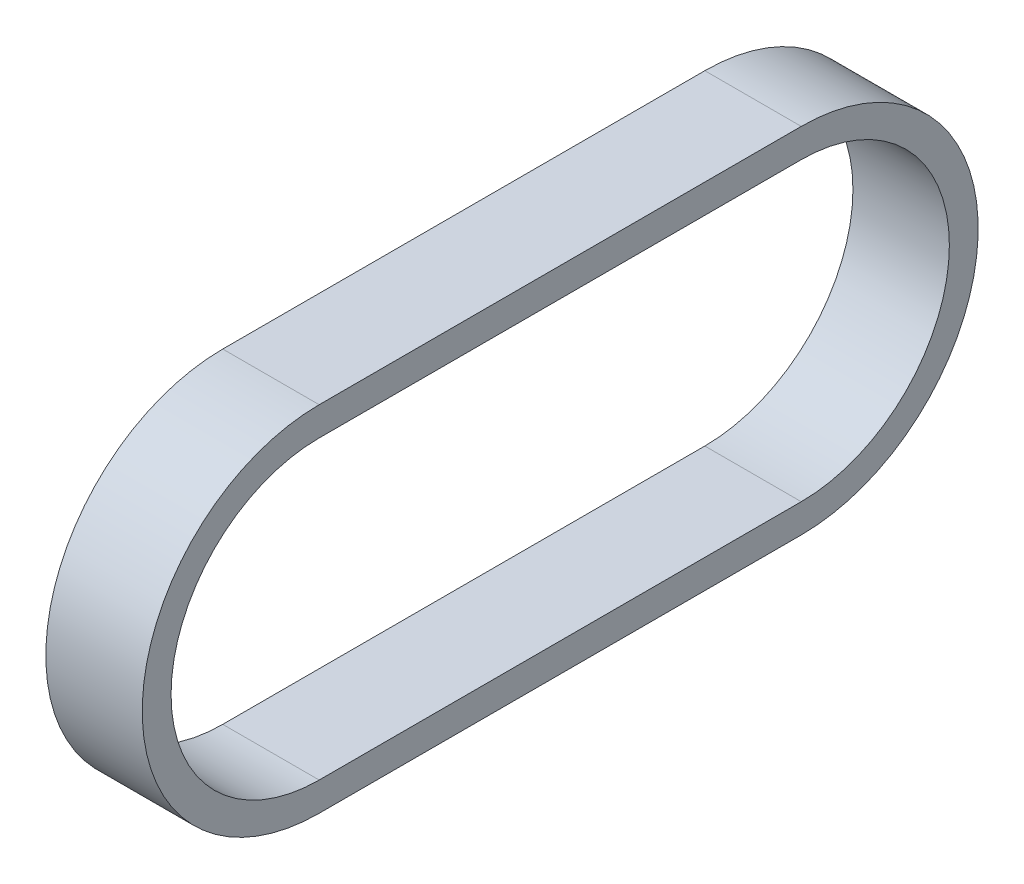
SolidWorks part; units mm, degrees
ref_plane "Front" through (0, 0, 0) normal (0, 0, 1) x (1, 0, 0)
ref_plane "Top" through (0, 0, 0) normal (0, 1, 0) x (1, 0, 0)
ref_plane "Right" through (0, 0, 0) normal (1, 0, 0) x (0, 0, -1)
sketch "Sketch1" plane through (0, 0, 0) normal (1, 0, 0) x (0, 0, -1)
  line L0 (-21.2471, 0) -> (21.2471, 0) construction
  line L1 (-21.2471, 14.3256) -> (21.2471, 14.3256)
  line L2 (-21.2471, -14.3256) -> (21.2471, -14.3256)
  arc A0 (-21.2471, 14.3256) -> (-21.2471, -14.3256) centre (-21.2471, 0) ccw
  arc A1 (21.2471, -14.3256) -> (21.2471, 14.3256) centre (21.2471, 0) ccw
  point P2 (0, 0)
  dimension "D2" = 28.6512
  dimension "D1" = 42.4942
extrude "Extrude-Thin1" add sketch "Sketch1" along normal blind 8.5 thin thin type mid plane wall 2.54
